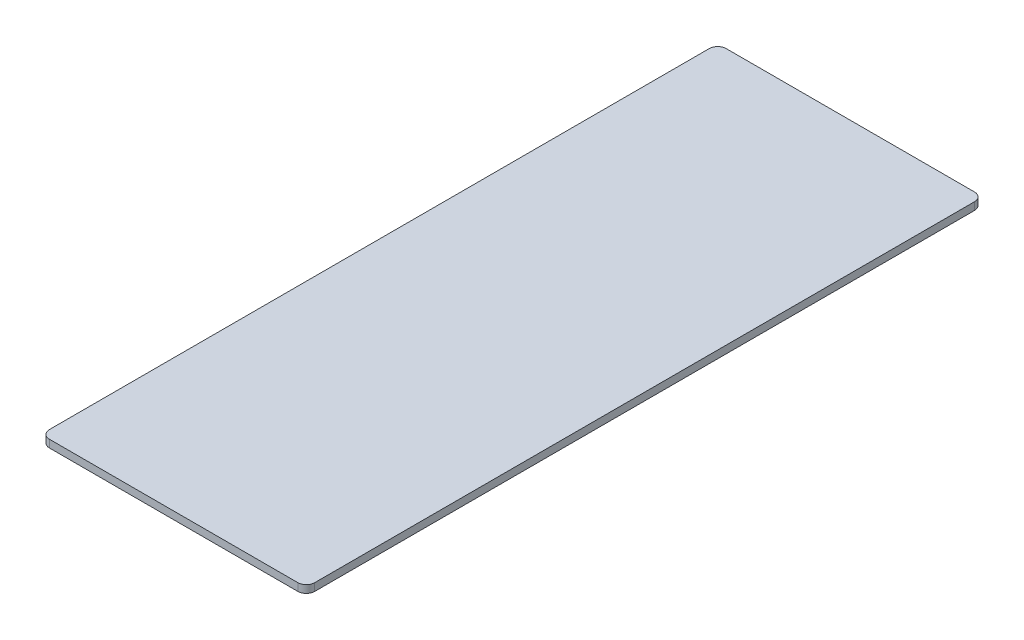
SolidWorks part; units mm, degrees
material "Acrylic (Medium-high impact)"
ref_plane "Front Plane" through (0, 0, 0) normal (0, 0, 1) x (1, 0, 0)
ref_plane "Top Plane" through (0, 0, 0) normal (0, 1, 0) x (1, 0, 0)
ref_plane "Right Plane" through (0, 0, 0) normal (1, 0, 0) x (0, 0, -1)
sketch "Sketch1" plane through (0, 0, 0) normal (0, 1, 0) x (1, 0, 0)
  line L1 (0, 0) -> (156.8, 0)
  line L2 (0, 0) -> (0, 400)
  line L3 (0, 400) -> (156.8, 400)
  line L4 (156.8, 0) -> (156.8, 400)
  dimension "D1" = 156.8
  dimension "D2" = 400
extrude "Boss-Extrude1" add sketch "Sketch1" along normal blind 4.5
fillet "Fillet1" radius 5 4 edges at (0, 2.25, -400) (0, 2.25, 0) (156.8, 2.25, -400) (156.8, 2.25, 0)
